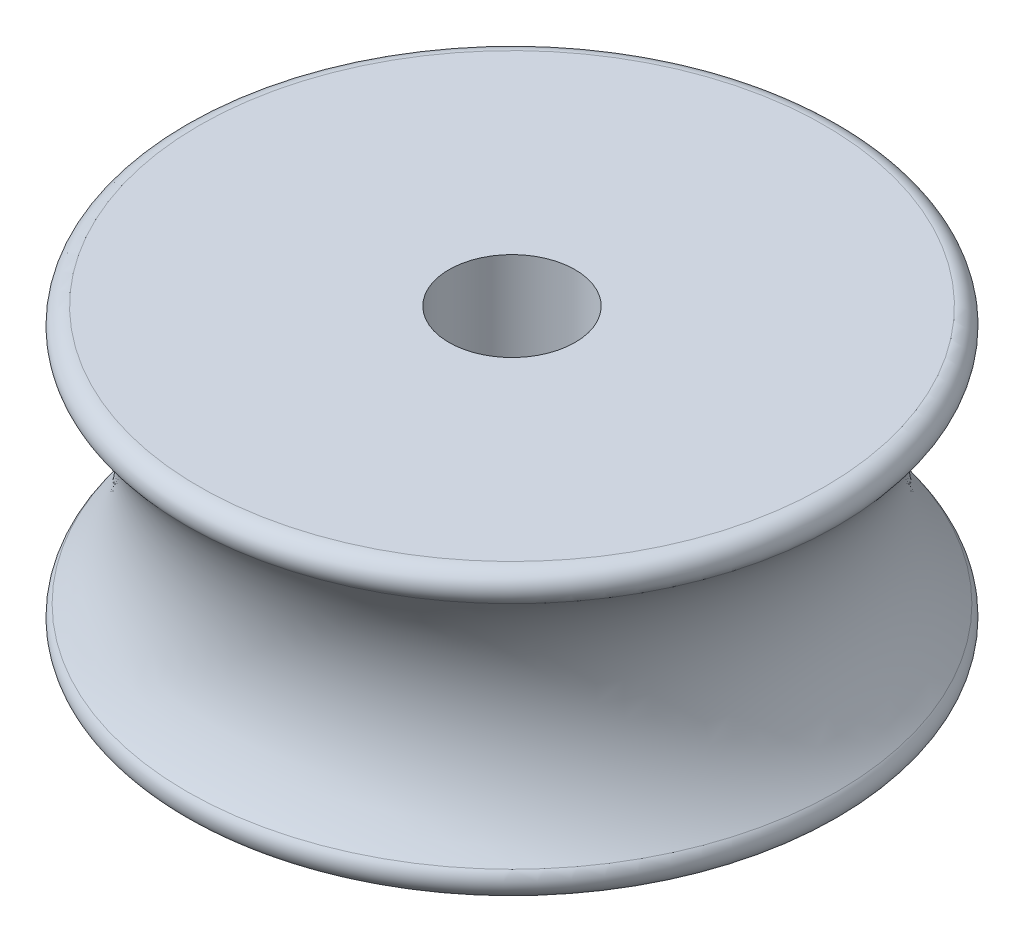
SolidWorks part; units mm, degrees
ref_plane "Front Plane" through (0, 0, 0) normal (0, 0, 1) x (1, 0, 0)
ref_plane "Top Plane" through (0, 0, 0) normal (0, 1, 0) x (1, 0, 0)
ref_plane "Right Plane" through (0, 0, 0) normal (1, 0, 0) x (0, 0, -1)
sketch "Sketch1" plane through (0, 0, 0) normal (0, 0, 1) x (1, 0, 0)
  line L0 (0, 0) -> (-1, 0) construction
  line L1 (0, 0) -> (18, 0) construction
  line L2 (18, -6) -> (18, 6)
  line L3 (18, 6) -> (1.562, 6)
  line L4 (18, -6) -> (1.562, -6)
  line L5 (15.35, -6) -> (15.35, 6)
  arc A0 (1.562, -6) -> (1.562, 6) centre (0, 0) ccw construction
  arc A1 (3.9799, -6) -> (3.9799, 6) centre (0, 0) ccw construction
  arc A2 (2.9799, -6) -> (2.9799, 6) centre (-1, 0) ccw
  point P10 (18, 0)
  point P16 (15.35, 0)
  dimension "D1" = 12.4
  dimension "D2" = 14.4
  dimension "D4" = 14.4
  dimension "D3" = 1
  dimension "D5" = 12
  dimension "D6" = 18
  dimension "D7" = 2.65
revolve "Revolve1" add sketch "Sketch1" angle 360 about L2
fillet "Fillet3" radius 0.7 2 edges at (33.0201, -6, 0) (33.0201, 6, 0)
